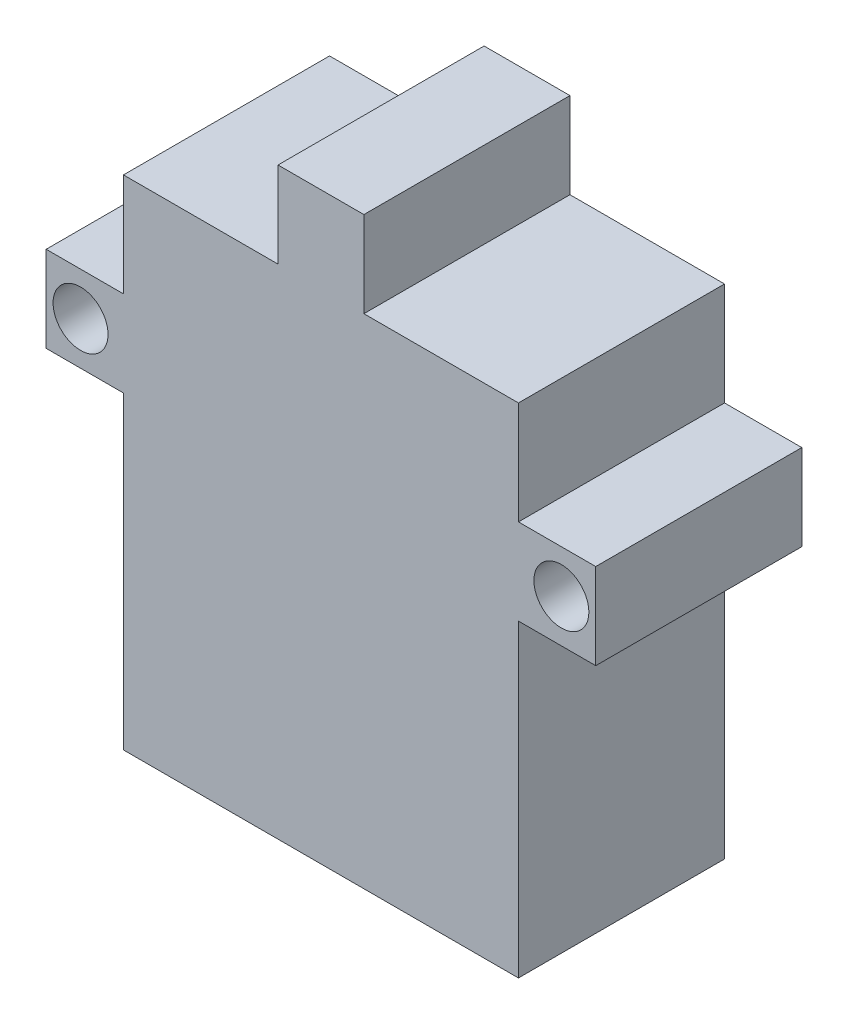
SolidWorks part; units mm, degrees
ref_plane "前视基准面" through (0, 0, 0) normal (0, 0, 1) x (1, 0, 0)
ref_plane "上视基准面" through (0, 0, 0) normal (0, 1, 0) x (1, 0, 0)
ref_plane "右视基准面" through (0, 0, 0) normal (1, 0, 0) x (0, 0, -1)
other "Configuration Table"
sketch "草图1" plane through (0, 0, 0) normal (0, 0, 1) x (1, 0, 0)
  line L0 (11.5, 0) -> (11.5, 18)
  line L1 (11.5, 18) -> (16, 18)
  line L2 (16, 18) -> (16, 23)
  line L3 (16, 23) -> (11.5, 23)
  line L4 (11.5, 23) -> (11.5, 29)
  line L5 (11.5, 29) -> (2.5, 29)
  line L6 (2.5, 29) -> (2.5, 34)
  line L7 (2.5, 34) -> (-2.5, 34)
  line L8 (-2.5, 34) -> (-2.5, 29)
  line L9 (-2.5, 29) -> (-11.5, 29)
  line L10 (-11.5, 29) -> (-11.5, 23)
  line L11 (-11.5, 23) -> (-16, 23)
  line L12 (-16, 23) -> (-16, 18)
  line L13 (-16, 18) -> (-11.5, 18)
  line L14 (-11.5, 18) -> (-11.5, 0)
  line L15 (-11.5, 0) -> (11.5, 0)
  circle A0 centre (14, 20.5) radius 1.6
  circle A1 centre (-14, 20.5) radius 1.6
extrude "凸台-拉伸1" add sketch "草图1" along normal mid plane 12
